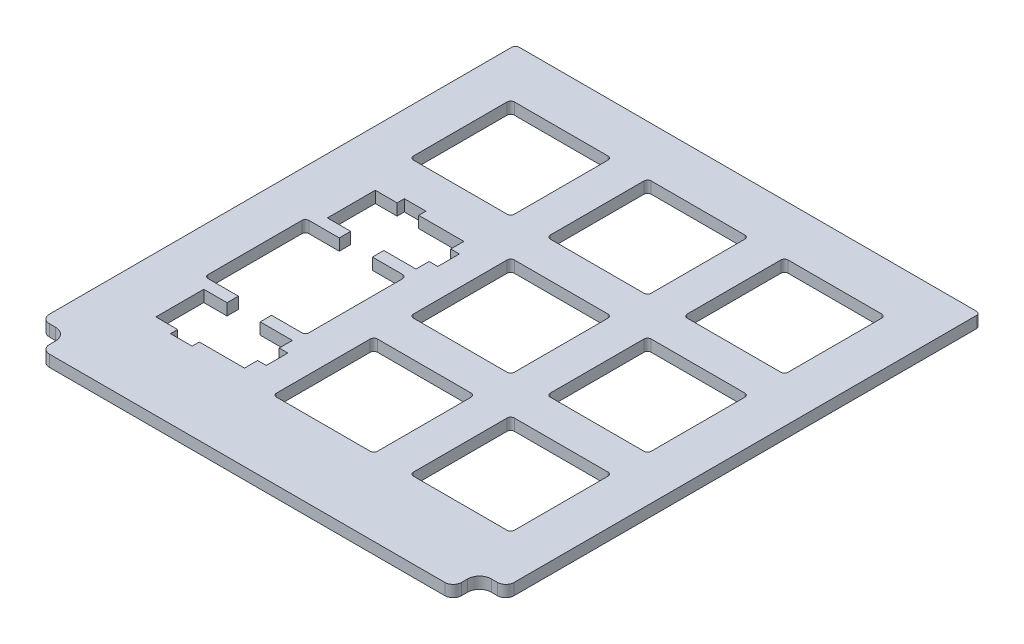
SolidWorks part; units mm, degrees
ref_plane "前视基准面" through (0, 0, 0) normal (0, 0, 1) x (1, 0, 0)
ref_plane "上视基准面" through (0, 0, 0) normal (0, 1, 0) x (1, 0, 0)
ref_plane "右视基准面" through (0, 0, 0) normal (1, 0, 0) x (0, 0, -1)
sketch "草图1" plane through (0, 0, 0) normal (0, 1, 0) x (1, 0, 0)
  line L0 (-12.5008, 61.2283) -> (51.9992, 61.2283)
  line L5 (51.9992, 61.2283) -> (51.9992, -3.4717)
  line L6 (-12.5008, 61.2283) -> (-12.5008, -3.4717)
  line L19 (50.8492, 119.1658) -> (49.9992, 119.1658)
  line L20 (48.3492, 120.8158) -> (48.3492, 121.6658)
  line L21 (47.1992, 122.8158) -> (-7.7008, 122.8158)
  line L22 (-8.8508, 121.6658) -> (-8.8508, 120.8158)
  line L23 (-10.5008, 119.1658) -> (-11.3508, 119.1658)
  line L24 (-12.5008, 118.0158) -> (-12.5008, -3.4717)
  line L25 (-11.3508, -4.6217) -> (-10.5008, -4.6217)
  line L26 (-8.8508, -6.2717) -> (-8.8508, -7.1217)
  line L27 (-7.7008, -8.2717) -> (47.1992, -8.2717)
  line L28 (48.3492, -7.1217) -> (48.3492, -6.2717)
  line L29 (49.9992, -4.6217) -> (50.8492, -4.6217)
  line L30 (51.9992, -3.4717) -> (51.9992, 97.2055)
  line L37 (-11.3508, -4.6217) -> (-10.5008, -4.6217)
  line L38 (-8.8508, -6.2717) -> (-8.8508, -7.1217)
  line L39 (-7.7008, -8.2717) -> (47.1992, -8.2717)
  line L40 (48.3492, -7.1217) -> (48.3492, -6.2717)
  line L41 (49.9992, -4.6217) -> (50.8492, -4.6217)
  line L266 (50.9992, 117.4055) -> (51.9992, 117.4055)
  line L268 (51.9992, 117.4055) -> (51.9992, 118.0158)
  line L270 (51.9992, 97.2055) -> (50.9992, 97.2055)
  line L272 (50.9992, 97.2055) -> (50.9992, 117.4055)
  arc A14 (51.9992, 118.0158) -> (50.8492, 119.1658) centre (50.8492, 118.0158) ccw
  arc A15 (48.3492, 120.8158) -> (49.9992, 119.1658) centre (49.9992, 120.8158) ccw
  arc A16 (48.3492, 121.6658) -> (47.1992, 122.8158) centre (47.1992, 121.6658) ccw
  arc A17 (-7.7008, 122.8158) -> (-8.8508, 121.6658) centre (-7.7008, 121.6658) ccw
  arc A18 (-10.5008, 119.1658) -> (-8.8508, 120.8158) centre (-10.5008, 120.8158) ccw
  arc A19 (-11.3508, 119.1658) -> (-12.5008, 118.0158) centre (-11.3508, 118.0158) ccw
  arc A20 (-12.5008, -3.4717) -> (-11.3508, -4.6217) centre (-11.3508, -3.4717) ccw
  arc A21 (-8.8508, -6.2717) -> (-10.5008, -4.6217) centre (-10.5008, -6.2717) ccw
  arc A22 (-8.8508, -7.1217) -> (-7.7008, -8.2717) centre (-7.7008, -7.1217) ccw
  arc A23 (47.1992, -8.2717) -> (48.3492, -7.1217) centre (47.1992, -7.1217) ccw
  arc A24 (49.9992, -4.6217) -> (48.3492, -6.2717) centre (49.9992, -6.2717) ccw
  arc A25 (50.8492, -4.6217) -> (51.9992, -3.4717) centre (50.8492, -3.4717) ccw
  arc A32 (-12.5008, -3.4717) -> (-11.3508, -4.6217) centre (-11.3508, -3.4717) ccw
  arc A33 (-8.8508, -6.2717) -> (-10.5008, -4.6217) centre (-10.5008, -6.2717) ccw
  arc A34 (-8.8508, -7.1217) -> (-7.7008, -8.2717) centre (-7.7008, -7.1217) ccw
  arc A35 (47.1992, -8.2717) -> (48.3492, -7.1217) centre (47.1992, -7.1217) ccw
  arc A36 (49.9992, -4.6217) -> (48.3492, -6.2717) centre (49.9992, -6.2717) ccw
  arc A37 (50.8492, -4.6217) -> (51.9992, -3.4717) centre (50.8492, -3.4717) ccw
  dimension "D2" = 69.5
  dimension "D1" = 0
extrude "凸台-拉伸1" add sketch "草图1" along normal blind 1.6
sketch "草图2" plane through (0, 0, 0) normal (0, -1, 0) x (1, 0, 0)
  line L0 (19.7492, 25.7738) -> (19.7492, -89.1768) construction
  line L1 (-22.8684, -28.3158) -> (51.3053, -28.3158) construction
  line L5 (-9.5008, -57.5658) -> (48.9992, -57.5658)
  line L6 (-9.5008, 0.9342) -> (-9.5008, -57.5658)
  line L7 (48.9992, 0.9342) -> (-9.5008, 0.9342)
  line L8 (48.9992, -57.5658) -> (48.9992, 0.9342)
  line L9 (-9.5008, -57.5658) -> (48.9992, -57.5658) construction
  line L10 (-9.5008, 0.9342) -> (-9.5008, -57.5658) construction
  line L11 (48.9992, 0.9342) -> (-9.5008, 0.9342) construction
  line L12 (48.9992, -57.5658) -> (48.9992, 0.9342) construction
  line L16 (45.7492, -16.3158) -> (31.7492, -16.3158)
  line L37 (45.7492, -16.3158) -> (45.7492, -2.3158)
  line L38 (45.7492, -2.3158) -> (31.7492, -2.3158)
  line L39 (31.7492, -16.3158) -> (31.7492, -2.3158)
  line L40 (45.7492, -16.3158) -> (31.7492, -2.3158) construction
  line L41 (45.7492, -2.3158) -> (31.7492, -16.3158) construction
  point P4 (38.7492, -9.3158)
  dimension "D2" = 14
  dimension "D3" = 19
  dimension "D4" = 19
  dimension "D1" = 0
extrude "切除-拉伸1" cut sketch "草图2" against normal up to next
fillet "圆角1" radius 0.5 4 edges at (45.7492, 0.8, -2.3158) (31.7492, 0.8, -2.3158) (31.7492, 0.8, -16.3158) (45.7492, 0.8, -16.3158)
pattern_linear "阵列(线性)2" count 3 spacing 19 along (0, 0, -1) count 3 spacing 19 along (-1, 0, 0) skipping (0, 2), (1, 2) of "圆角1", "切除-拉伸1"
sketch "草图3" plane through (0, 1.6, 0) normal (0, 1, 0) x (1, 0, 0)
  line L0 (-24.3873, 18.8158) -> (58.3219, 18.8158) construction
  line L1 (0.7492, -13.1729) -> (0.7492, 58.2769) construction
  line L2 (-6.2508, 12.3158) -> (-6.2508, 25.3158)
  line L3 (7.7492, 25.3158) -> (7.7492, 12.3158)
  line L4 (-5.7508, 25.8158) -> (-1.5508, 25.8158)
  line L9 (-6.2508, 25.8158) -> (7.7492, 11.8158) construction
  line L10 (-6.2508, 11.8158) -> (7.7492, 25.8158) construction
  line L11 (-1.5508, 25.8158) -> (-1.5508, 27.3958)
  line L12 (-4.7808, 27.3958) -> (-1.5508, 27.3958)
  line L13 (-4.7808, 27.3958) -> (-4.7808, 34.0458)
  line L14 (-4.7808, 34.0458) -> (-1.7508, 34.0458)
  line L15 (-1.7508, 34.0458) -> (-1.7508, 35.0458)
  line L16 (-1.7508, 35.0458) -> (1.2492, 35.0458)
  line L17 (1.2492, 35.0458) -> (1.2492, 34.0458)
  line L18 (1.2492, 34.0458) -> (7.5192, 34.0458)
  line L19 (7.5192, 34.0458) -> (7.5192, 32.2208)
  line L20 (7.5192, 32.2208) -> (8.7192, 32.2208)
  line L21 (8.7192, 32.2208) -> (8.7192, 29.2208)
  line L22 (8.7192, 29.2208) -> (7.5192, 29.2208)
  line L23 (7.5192, 29.2208) -> (7.5192, 27.3958)
  line L24 (7.5192, 27.3958) -> (3.0492, 27.3958)
  line L25 (3.0492, 27.3958) -> (3.0492, 25.8158)
  line L26 (3.0492, 25.8158) -> (7.2492, 25.8158)
  line L27 (3.0492, 11.8158) -> (7.2492, 11.8158)
  line L28 (3.0492, 10.2358) -> (3.0492, 11.8158)
  line L29 (7.5192, 10.2358) -> (3.0492, 10.2358)
  line L30 (7.5192, 8.4108) -> (7.5192, 10.2358)
  line L31 (8.7192, 8.4108) -> (7.5192, 8.4108)
  line L32 (8.7192, 5.4108) -> (8.7192, 8.4108)
  line L33 (7.5192, 5.4108) -> (8.7192, 5.4108)
  line L34 (7.5192, 3.5858) -> (7.5192, 5.4108)
  line L35 (1.2492, 3.5858) -> (7.5192, 3.5858)
  line L36 (1.2492, 2.5858) -> (1.2492, 3.5858)
  line L37 (-1.7508, 2.5858) -> (1.2492, 2.5858)
  line L38 (-1.7508, 3.5858) -> (-1.7508, 2.5858)
  line L39 (-4.7808, 3.5858) -> (-1.7508, 3.5858)
  line L40 (-4.7808, 10.2358) -> (-4.7808, 3.5858)
  line L41 (-4.7808, 10.2358) -> (-1.5508, 10.2358)
  line L42 (-1.5508, 11.8158) -> (-1.5508, 10.2358)
  line L43 (-5.7508, 11.8158) -> (-1.5508, 11.8158)
  arc A0 (-6.2508, 25.3158) -> (-5.7508, 25.8158) centre (-5.7508, 25.3158) cw
  arc A1 (7.2492, 25.8158) -> (7.7492, 25.3158) centre (7.2492, 25.3158) cw
  arc A2 (7.2492, 11.8158) -> (7.7492, 12.3158) centre (7.2492, 12.3158) ccw
  arc A3 (-6.2508, 12.3158) -> (-5.7508, 11.8158) centre (-5.7508, 12.3158) ccw
  point P4 (0.7492, 18.8158)
  point P5 (0.7492, 18.8158)
  dimension "D1" = 14
  dimension "D2" = 4.2
  dimension "D3" = 1.58
  dimension "D4" = 3.23
  dimension "D5" = 6.65
  dimension "D6" = 3.03
  dimension "D7" = 3
  dimension "D8" = 1
  dimension "D9" = 6.27
  dimension "D10" = 3
  dimension "D11" = 1.2
  dimension "D12" = 0.5
  dimension "D13" = 13
  dimension "D14" = 45
  dimension "D15" = 4.47
extrude "切除-拉伸3" cut sketch "草图3" against normal up to surface (1.6 mm away) up to face at (38.7492, 0, -28.3158)
fillet "圆角2" radius 0.5 2 edges at (51.9992, 0.8, -61.2283) (-12.5008, 0.8, -61.2283)
